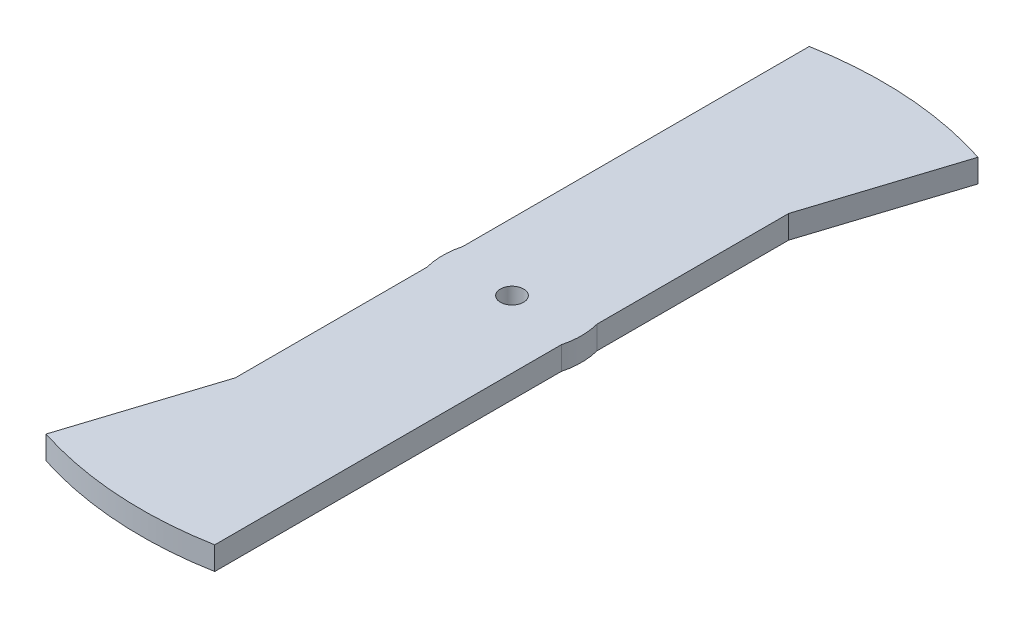
SolidWorks part; units mm, degrees
material "AISI 316 Stainless Steel Sheet (SS)"
ref_plane "Front Plane" through (0, 0, 0) normal (0, 0, 1) x (1, 0, 0)
ref_plane "Top Plane" through (0, 0, 0) normal (0, 1, 0) x (1, 0, 0)
ref_plane "Right Plane" through (0, 0, 0) normal (1, 0, 0) x (0, 0, -1)
sketch "Sketch1" plane through (0, 0, 0) normal (0, 1, 0) x (1, 0, 0)
  line L0 (0, 19.05) -> (0, 101.6) construction
  line L1 (-18.415, 99.9172) -> (-18.415, 4.8775)
  line L2 (18.415, 4.8775) -> (18.415, 57.4456)
  line L3 (18.415, 57.4456) -> (31.0147, 96.7504)
  line L4 (18.415, -99.9172) -> (18.415, -4.8775)
  line L5 (-18.415, -57.4456) -> (-31.0147, -96.7504)
  line L6 (-18.415, -4.8775) -> (-18.415, -57.4456)
  circle A0 centre (0, 0) radius 3.175
  circle A1 centre (0, 0) radius 19.05 construction
  circle A2 centre (0, 0) radius 101.6 construction
  arc A3 (-18.415, 99.9172) -> (31.0147, 96.7504) centre (0, 0) cw
  circle A4 centre (0, 0) radius 60.325 construction
  arc A5 (18.415, -99.9172) -> (-31.0147, -96.7504) centre (0, 0) cw
  arc A6 (-18.415, 4.8775) -> (-18.415, -4.8775) centre (0, 0) ccw
  arc A7 (18.415, 4.8775) -> (18.415, -4.8775) centre (0, 0) cw
  point P9 (18.415, 4.8775)
  point P15 (0, 60.325)
  point P23 (0, 0)
  dimension "D1" = 6.35
  dimension "D2" = 38.1
  dimension "D3" = 203.2
  dimension "D4" = 36.83
  dimension "D6" = 2
extrude "Boss-Extrude1" add sketch "Sketch1" along normal blind 6.35 contours A7 L2 L3 A3 L1 A6 L6 L5 A5 L4 A0
